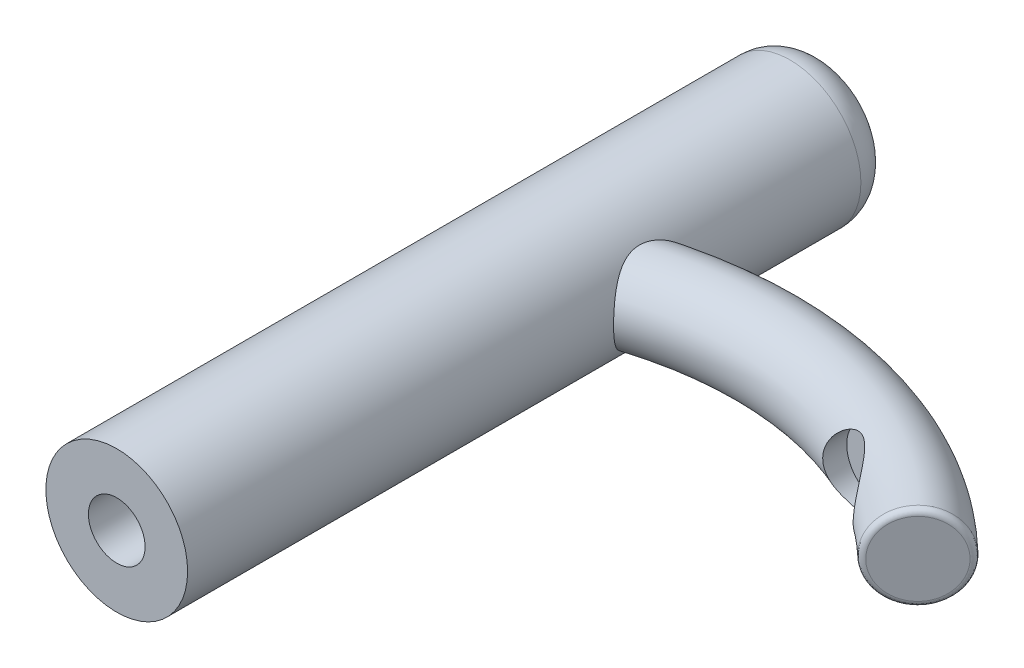
SolidWorks part; units mm, degrees
ref_plane "Front Plane" through (0, 0, 0) normal (0, 0, 1) x (1, 0, 0)
ref_plane "Top Plane" through (0, 0, 0) normal (0, 1, 0) x (1, 0, 0)
ref_plane "Right Plane" through (0, 0, 0) normal (1, 0, 0) x (0, 0, -1)
sketch "Sketch1" plane through (0, 0, 0) normal (0, 1, 0) x (1, 0, 0)
  line L0 (0, 0) -> (0, 11383.6344) construction
  line L1 (0, 0) -> (-11383.6344, 0) construction
  line L2 (0, 475) -> (20, 475)
  line L3 (20, 0) -> (50, 0)
  line L4 (20, 0) -> (20, 475)
  line L5 (0, 500) -> (25, 500)
  line L6 (50, 0) -> (50, 475)
  line L7 (0, 500) -> (0, 475)
  arc A0 (25, 500) -> (50, 475) centre (25, 475) cw
  point P13 (50, 500)
  dimension "D5" = 25
  dimension "D1" = 20
  dimension "D2" = 50
  dimension "D3" = 500
  dimension "D4" = 25
revolve "Revolve1" add sketch "Sketch1" angle 360 about L0
ref_plane "Plane2" through (300, 0, 0) normal (1, 0, 0) x (0, 0, -1)
sketch "Sketch2" plane through (300, 0, 0) normal (1, 0, 0) x (0, 0, -1)
  circle A0 centre (265.2453, 0) radius 25
  dimension "D1" = 50
ref_plane "Plane3" through (0, 0, 0) normal (1, 0, 0) x (0, 0, -1)
sketch "Sketch3" plane through (0, 0, 0) normal (1, 0, 0) x (0, 0, -1)
  circle A0 centre (312.6752, 0) radius 25
  dimension "D1" = 50
sketch3d "3DSketch2"
  arc A0 (0, 0, -312.6752) -> (300, 0, -265.2453) centre (117.0441, 0, -80.51) cw
  point P2 (117.0441, -260, -80.51)
  dimension "D1" = 260
sweep "Sweep1" add path "3DSketch2" circular profile diameter 60 parameters "D3"=60
sketch "Sketch32" plane through (0, 0, 0) normal (0, 0, 1) x (1, 0, 0)
  circle A0 centre (230, 0) radius 25
  dimension "D1" = 50
  dimension "D2" = 230
extrude "Cut-Extrude1" cut sketch "Sketch32" against normal blind 310
fillet "Fillet1" radius 4 1 edges at (321.1103, 0, -286.5609)
